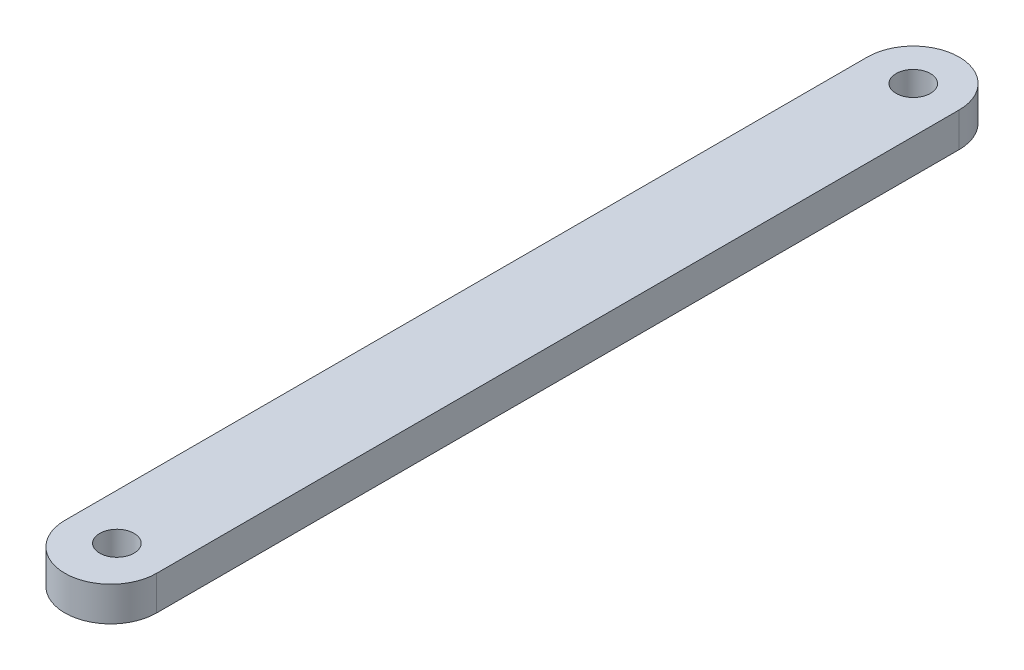
SolidWorks part; units mm, degrees
ref_plane "Alzado" through (0, 0, 0) normal (0, 0, 1) x (1, 0, 0)
ref_plane "Planta" through (0, 0, 0) normal (0, 1, 0) x (1, 0, 0)
ref_plane "Vista lateral" through (0, 0, 0) normal (1, 0, 0) x (0, 0, -1)
sketch "Croquis1" plane through (0, 0, 0) normal (0, 0, 1) x (1, 0, 0)
  line L0 (41815.5435, -364.9395) -> (41815.5435, -434.9395)
  line L1 (41807.5435, -364.9395) -> (41807.5435, -434.9395)
  circle A0 centre (41811.5431, -365.4748) radius 1.5
  arc A2 (41815.5435, -364.9395) -> (41807.5435, -364.9395) centre (41811.5435, -364.9395) ccw
  circle A3 centre (41811.5435, -434.9395) radius 1.5
  arc A4 (41807.5435, -434.9395) -> (41815.5435, -434.9395) centre (41811.5435, -434.9395) ccw
extrude "Saliente-Extruir1" add sketch "Croquis1" along normal blind 3
move or copy body "Sólido-Mover/Copiar1" bodies to move or copy 101 copy no rotation origin (0, -399.9395, 1.5) rotation axis (1, 0, 0) rotation angle 90
